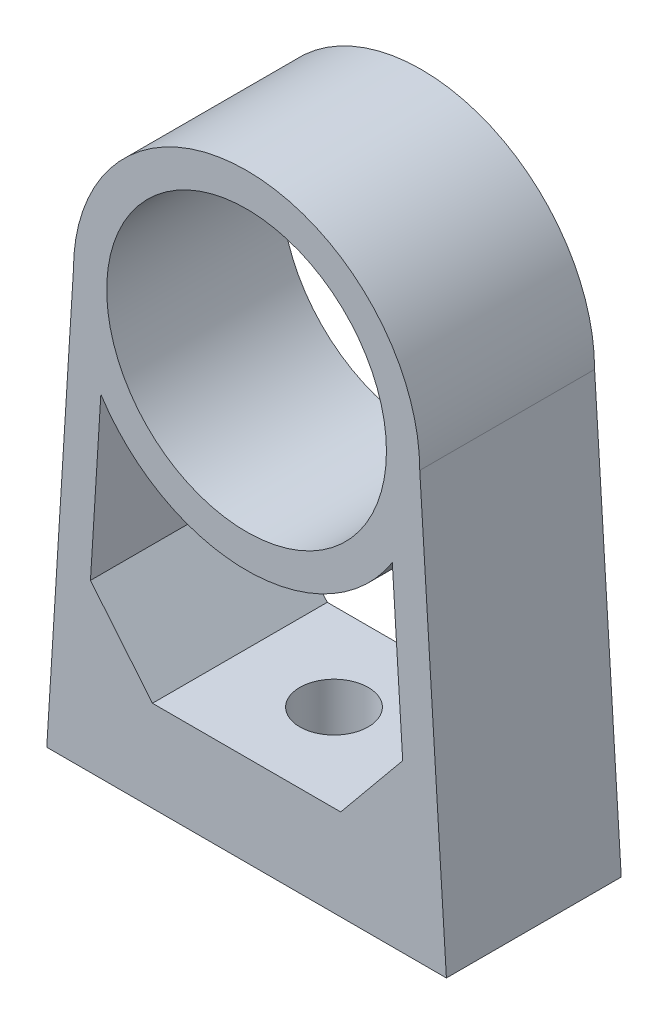
SolidWorks part; units mm, degrees
ref_plane "Front Plane" through (0, 0, 0) normal (0, 0, 1) x (1, 0, 0)
ref_plane "Top Plane" through (0, 0, 0) normal (0, 1, 0) x (1, 0, 0)
ref_plane "Right Plane" through (0, 0, 0) normal (1, 0, 0) x (0, 0, -1)
sketch "Sketch1" plane through (0, 0, 0) normal (0, 0, 1) x (1, 0, 0)
  line L0 (-19.05, -40.64) -> (19.05, -40.64)
  line L1 (0, 13.335) -> (-25.3137, 13.335) construction
  line L2 (0, 0) -> (0, -40.64) construction
  line L3 (-16.51, 0) -> (-19.05, -40.64)
  line L4 (16.51, 0) -> (19.05, -40.64)
  line L5 (-13.8925, -8.9206) -> (-14.8838, -24.7803)
  line L6 (13.8925, -8.9206) -> (14.8838, -24.7803)
  line L7 (-8.9738, -31.9687) -> (8.9738, -31.9687)
  line L8 (8.9738, -31.9687) -> (14.8838, -24.7803)
  line L10 (-14.8838, -24.7803) -> (-8.9738, -31.9687)
  circle A0 centre (0, 0) radius 13.335
  arc A1 (-13.8925, -8.9206) -> (13.8925, -8.9206) centre (0, 0) ccw
  arc A2 (16.51, 0) -> (-16.51, 0) centre (0, 0) ccw
  point P6 (0, -40.64)
  point P19 (0, -31.9687)
  dimension "D1" = 26.67
  dimension "D3" = 3.175
  dimension "D2" = 53.975
  dimension "D4" = 38.1
extrude "Boss-Extrude1" add sketch "Sketch1" along normal blind 16.6687
hole_wizard "1/4 Clearance Hole1" positions "Sketch2" profile "Sketch3" hole size "1/4" standard "ANSI Inch"
sketch "Sketch2" plane through (0, -40.64, 0) normal (0, -1, 0) x (-1, 0, 0)
  line L0 (19.05, -16.6687) -> (-19.05, 0) construction
  point P7 (0, -8.3344)
sketch "Sketch3" plane through (0, -40.64, 8.3344) normal (1, 0, 0) x (0, 0, -1)
  line L0 (0, 0) -> (0, 8.6713)
  line L1 (0, 8.6713) -> (3.2639, 8.6713)
  line L2 (3.2639, 8.6713) -> (3.2639, 0)
  line L5 (3.2639, 0) -> (0, 0)
  line L11 (0, -6.35) -> (0, 107.95) construction
  dimension "Thru Hole Dia." = 6.5278
  dimension "Thru Hole Depth" = 8.6713
